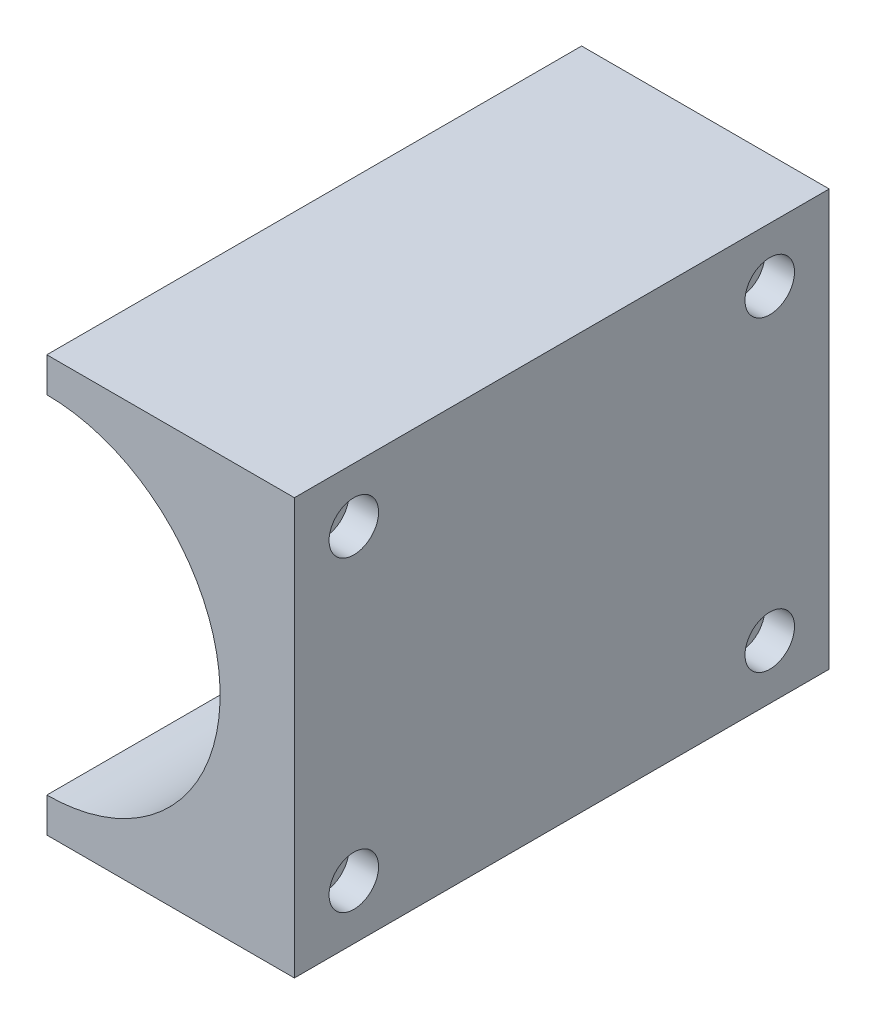
SolidWorks part; units mm, degrees
material "ABS PC"
ref_plane "Front Plane" through (0, 0, 0) normal (0, 0, 1) x (1, 0, 0)
ref_plane "Top Plane" through (0, 0, 0) normal (0, 1, 0) x (1, 0, 0)
ref_plane "Right Plane" through (0, 0, 0) normal (1, 0, 0) x (0, 0, -1)
sketch "Sketch1" plane through (0, 0, 0) normal (0, 0, 1) x (1, 0, 0)
  line L0 (24.5, -21.5) -> (-7.5, -21.5) construction
  line L2 (-7.5, 21.5) -> (24.5, 21.5) construction
  line L5 (-7.5, 21.5) -> (24.5, 21.5) construction
  line L6 (24, 21) -> (24, -21)
  line L7 (24, -21) -> (-1, -21)
  line L8 (-1, -21) -> (-1, 21)
  line L9 (-1, 21) -> (24, 21)
  line L10 (24.5, -21.5) -> (-7.5, -21.5) construction
  line L11 (24.5, 21.5) -> (24.5, -21.5) construction
  line L12 (24.5, 21.5) -> (24.5, -21.5) construction
  dimension "D1" = 25
  dimension "D2" = 0.5
  dimension "D3" = 0.5
  dimension "D4" = 0.5
extrude "Boss-Extrude1" add sketch "Sketch1" against normal up to surface (54 mm away)
sketch "Sketch2" plane through (0, 0, -54) normal (0, 0, -1) x (-1, 0, 0)
  line L0 (1, -21) -> (1, 21) construction
  circle A0 centre (1, 0) radius 18.5
  dimension "D1" = 37
extrude "Cut-Extrude1" cut sketch "Sketch2" against normal up to surface (28 mm away)
sketch "Sketch3" plane through (0, 0, 0) normal (0, 0, 1) x (1, 0, 0)
  line L0 (-1, 21) -> (-1, -21) construction
  circle A0 centre (-1, 0) radius 17.5
  dimension "D1" = 35
extrude "Cut-Extrude2" cut sketch "Sketch3" against normal up to next
sketch "Sketch4" plane through (24, 0, 0) normal (1, 0, 0) x (0, 0, -1)
  line L0 (6, 15.5) -> (6, -15.5) construction
  line L1 (6, 15.5) -> (48, 15.5) construction
  line L2 (6, -15.5) -> (48, -15.5) construction
  line L3 (48, 15.5) -> (48, -15.5) construction
  line L4 (54, 21) -> (54, -21) construction
  line L5 (0, 27) -> (0, -27) construction
  line L6 (54, -21) -> (0, -21) construction
  line L7 (54, 21) -> (0, 21) construction
  circle A0 centre (6, 15.5) radius 2.5
  circle A1 centre (48, 15.5) radius 2.5
  circle A2 centre (6, -15.5) radius 2.5
  circle A3 centre (48, -15.5) radius 2.5
  dimension "D5" = 5
  dimension "D6" = 5
  dimension "D7" = 5
  dimension "D8" = 5
  dimension "D1" = 6
  dimension "D2" = 6
  dimension "D3" = 5.5
  dimension "D4" = 5.5
extrude "Cut-Extrude3" cut sketch "Sketch4" against normal blind 3
